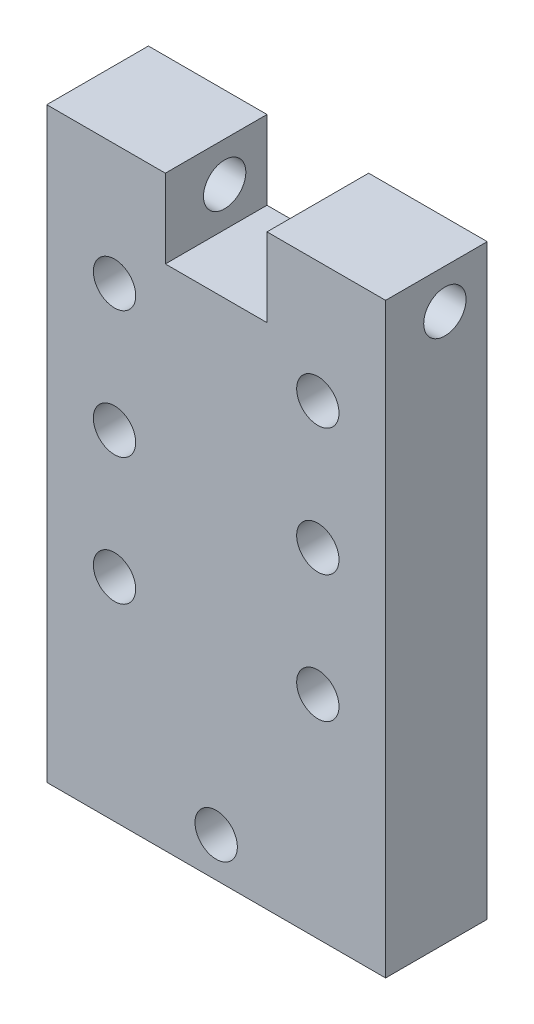
SolidWorks part; units mm, degrees
ref_plane "前视基准面" through (0, 0, 0) normal (0, 0, 1) x (1, 0, 0)
ref_plane "上视基准面" through (0, 0, 0) normal (0, 1, 0) x (1, 0, 0)
ref_plane "右视基准面" through (0, 0, 0) normal (1, 0, 0) x (0, 0, -1)
sketch "草图1" plane through (0, 0, 0) normal (0, 0, 1) x (1, 0, 0)
  line L1 (-20, -34.641) -> (20, -34.641)
  line L2 (-20, -34.641) -> (-20, 34.641)
  line L3 (-20, 34.641) -> (20, 34.641)
  line L4 (20, -34.641) -> (20, 34.641)
  line L5 (-20, -34.641) -> (20, 34.641) construction
  line L6 (-20, 34.641) -> (20, -34.641) construction
  circle A0 centre (0, 0) radius 40 construction
  circle A1 centre (0, 30) radius 2.5 construction
  circle A2 centre (0, -30) radius 2.5 construction
  dimension "D1" = 80
  dimension "D3" = 5
  dimension "D4" = 5
  dimension "D2" = 40
  dimension "D5" = 30
  dimension "D6" = 30
extrude "凸台-拉伸1" add sketch "草图1" along normal blind 12
sketch "草图2" plane through (0, 0, 12) normal (0, 0, 1) x (1, 0, 0)
  line L0 (20, 34.641) -> (-20, 34.641) construction
  line L1 (-6, 25.359) -> (6, 25.359)
  line L2 (-6, 25.359) -> (-6, 34.641)
  line L3 (-6, 34.641) -> (6, 34.641)
  line L4 (6, 25.359) -> (6, 34.641)
  line L5 (-6, 25.359) -> (6, 34.641) construction
  line L6 (-6, 34.641) -> (6, 25.359) construction
  circle A1 centre (0, -30) radius 2.5
  point P0 (0, 30)
  point P1 (0, 30)
  point P4 (0, 0)
  dimension "D1" = 5
  dimension "D4" = 12
  dimension "D2" = 30
  dimension "D3" = 30
extrude "切除-拉伸1" cut sketch "草图2" against normal blind 12
sketch "草图3" plane through (-20, 0, 0) normal (-1, 0, 0) x (0, 0, 1)
  line L0 (0, 34.641) -> (0, -34.641) construction
  circle A0 centre (5, 30) radius 2.5
  point P4 (0, 0)
  dimension "D1" = 30
  dimension "D2" = 5
extrude "切除-拉伸2" cut sketch "草图3" against normal blind 60
sketch "草图4" plane through (0, 0, 0) normal (0, 0, -1) x (-1, 0, 0)
  line L1 (0, 0) -> (0, 22.0256) construction
  circle A1 centre (-12, -9.641) radius 2.5
  circle A2 centre (-12, 5.359) radius 2.5
  circle A3 centre (-12, 20.359) radius 2.5
  circle A4 centre (12, 20.359) radius 2.5
  circle A5 centre (12, 5.359) radius 2.5
  circle A6 centre (12, -9.641) radius 2.5
  dimension "D2" = 5
  dimension "D3" = 5
  dimension "D4" = 5
  dimension "D7" = 15
  dimension "D8" = 15
  dimension "D9" = 12
  dimension "D10" = 12
extrude "切除-拉伸3" cut sketch "草图4" against normal blind 12
sketch "草图5" plane through (0, 0, 0) normal (0, 0, -1) x (-1, 0, 0)
  circle A9 centre (-12, -9.641) radius 4.5
  circle A10 centre (-12, -9.641) radius 4.5
  circle A12 centre (-12, 5.359) radius 4.5
  circle A13 centre (-12, 5.359) radius 4.5
  circle A15 centre (-12, 20.359) radius 4.5
  circle A16 centre (-12, 20.359) radius 4.5
  circle A21 centre (12, -9.641) radius 4.5
  circle A22 centre (12, -9.641) radius 4.5
  circle A24 centre (12, 5.359) radius 4.5
  circle A25 centre (12, 5.359) radius 4.5
  circle A27 centre (12, 20.359) radius 4.5
  circle A28 centre (12, 20.359) radius 4.5
  dimension "D2" = 2
  dimension "D3" = 2
  dimension "D4" = 2
  dimension "D6" = 2
  dimension "D7" = 2
  dimension "D8" = 2
extrude "切除-拉伸4" cut sketch "草图5" against normal blind 3
sketch "草图6" plane through (0, -34.641, 0) normal (0, -1, 0) x (1, 0, 0)
  line L1 (15, -12) -> (-15, -12) construction
  line L2 (15, -12) -> (15, 12) construction
  line L3 (15, 12) -> (-15, 12) construction
  line L4 (-15, -12) -> (-15, 12) construction
  line L5 (15, -12) -> (-15, 12) construction
  line L6 (15, 12) -> (-15, -12) construction
  line L7 (-20, 12) -> (20, 12) construction
  circle A0 centre (-10, 6) radius 2.5
  circle A1 centre (10, 6) radius 2.5
  point P0 (0, 0)
  dimension "D2" = 5
  dimension "D3" = 5
  dimension "D1" = 30
  dimension "D4" = 6
  dimension "D5" = 6
  dimension "D6" = 5
  dimension "D7" = 5
extrude "切除-拉伸5" cut sketch "草图6" against normal blind 10
